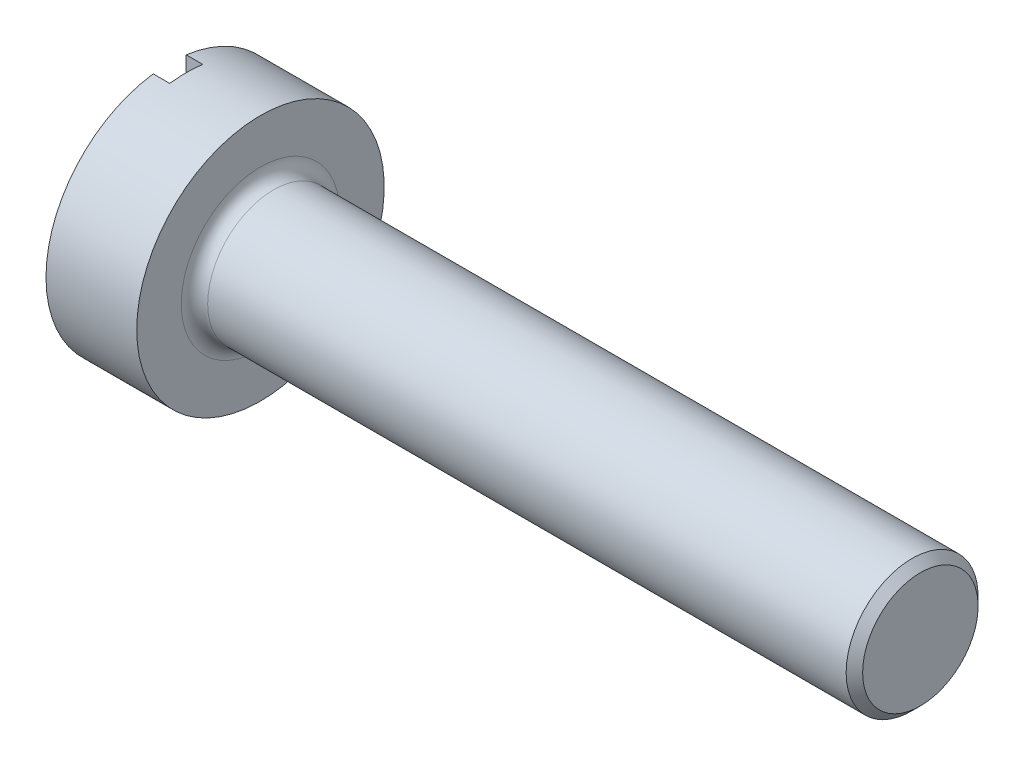
SolidWorks part; units mm, degrees
ref_plane "Front Plane" through (0, 0, 0) normal (0, 0, 1) x (1, 0, 0)
ref_plane "Top Plane" through (0, 0, 0) normal (0, 1, 0) x (1, 0, 0)
ref_plane "Right Plane" through (0, 0, 0) normal (1, 0, 0) x (0, 0, -1)
sketch "Sketch1" plane through (0, 0, 0) normal (0, 0, 1) x (1, 0, 0)
  line L0 (0, 0) -> (0, 1.5)
  line L1 (0, 1.5) -> (1.1, 1.5)
  line L2 (1.1, 1.5) -> (1.1, 0)
  line L3 (0, 0) -> (9.1, 0)
  line L4 (9.1, 0) -> (9.1, 0.8)
  line L5 (9.1, 0.8) -> (1.1, 0.8)
  dimension "D1" = 1.5
  dimension "D2" = 1.1
  dimension "D3" = 8
revolve "Revolve1" add sketch "Sketch1" angle 360 about L3
chamfer "Chamfer1" distance 0.1 angle 45 1 edges at (9.1, 0, 0.8)
fillet "Fillet1" radius 0.16 1 edges at (1.1, 0, 0.8)
sketch "Sketch2" plane through (0, 0, 0) normal (0, 1, 0) x (1, 0, 0)
  line L1 (0, 0) -> (0.2, 0)
  line L2 (0, 0) -> (0, 0.2)
  line L3 (0, 0.2) -> (0.2, 0.2)
  line L4 (0.2, 0) -> (0.2, 0.2)
  line L5 (0, 0) -> (0.2, 0)
  line L6 (0, 0) -> (0, -0.2)
  line L7 (0, -0.2) -> (0.2, -0.2)
  line L8 (0.2, 0) -> (0.2, -0.2)
extrude "Extrude1" cut sketch "Sketch2" against normal through all both and the other way through all contours L8 L1 L6 L7 | L1 L4 L3 L2
